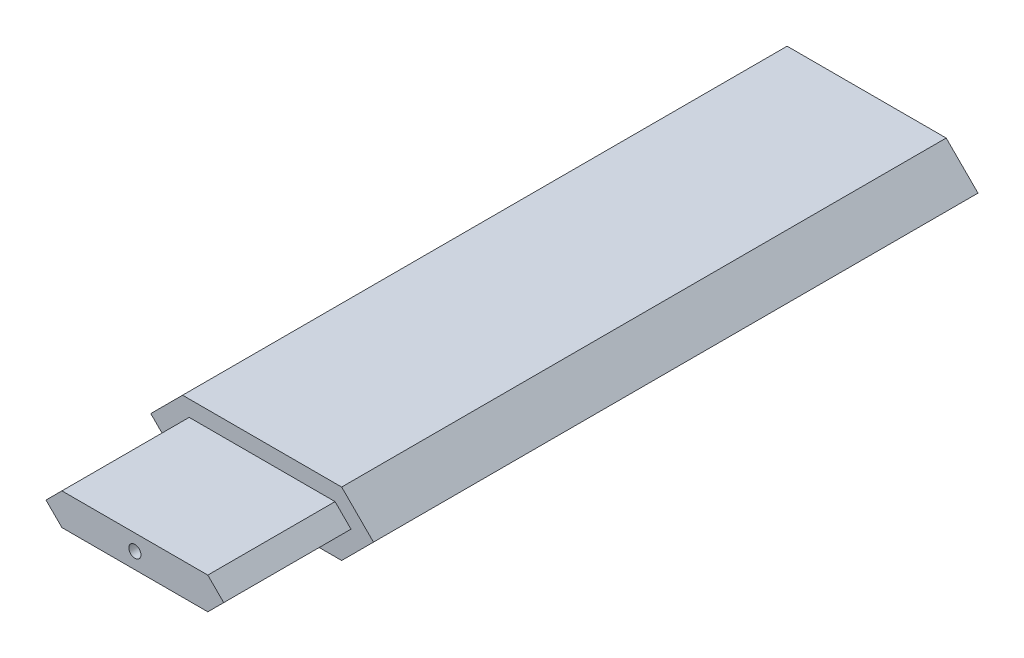
SolidWorks part; units mm, degrees
ref_plane "前视基准面" through (0, 0, 0) normal (0, 0, 1) x (1, 0, 0)
ref_plane "上视基准面" through (0, 0, 0) normal (0, 1, 0) x (1, 0, 0)
ref_plane "右视基准面" through (0, 0, 0) normal (1, 0, 0) x (0, 0, -1)
sketch "草图1" plane through (0, 0, 0) normal (0, 1, 0) x (1, 0, 0)
  line L0 (0, 0) -> (0, 690) construction
  line L1 (0, 690) -> (0, 630) construction
  line L2 (-35, 0) -> (35, 0)
  line L3 (-35, 0) -> (-35, 630)
  line L4 (-35, 630) -> (0, 690)
  line L5 (35, 630) -> (0, 690)
  line L6 (35, 0) -> (35, 630)
  dimension "D1" = 690
  dimension "D2" = 60
  dimension "D3" = 70
ref_plane "基准面1" through (0, 10, 0) normal (0, 1, 0) x (1, 0, 0)
sketch "草图4" plane through (0, 10, 0) normal (0, 1, 0) x (1, 0, 0)
  line L0 (25, 0) -> (-25, 0)
  line L1 (-25, 0) -> (-25, 630)
  line L2 (-25, 630) -> (0, 672.8571)
  line L3 (0, 0) -> (0, 690) construction
  line L4 (-35, 630) -> (0, 690) construction
  line L5 (0, -5.5) -> (0, 5.5) construction
  line L6 (25, 630) -> (0, 672.8571)
  line L7 (25, 0) -> (25, 630)
  point P2 (0, 0)
  dimension "D1" = 50
loft "放样1" add profiles "草图4", "草图1"
mirror "镜向1" about plane through (0, 0, 0) normal (0, 1, 0) of "放样1"
sketch "草图5" plane through (0, 0, 0) normal (0, 1, 0) x (1, 0, 0)
  line L0 (0, -30.5) -> (0, -55.5) construction
  line L1 (0, -55.5) -> (0, -30.5) construction
  line L2 (-79, -30.5) -> (79, -30.5) construction
  line L3 (0, -30.5) -> (0, 0) construction
  arc A0 (-66.3468, -65.1892) -> (66.3468, -65.1892) centre (0, -287.5) cw
  arc A1 (76.7912, -2.3877) -> (76.7912, -58.6123) centre (-101, -30.5) cw
  arc A2 (-76.7912, -2.3877) -> (-76.7912, -58.6123) centre (101, -30.5) ccw
  arc A4 (66.3468, -65.1892) -> (76.7912, -58.6123) centre (68.6918, -57.3316) ccw
  arc A5 (-66.3468, -65.1892) -> (-76.7912, -58.6123) centre (-68.6918, -57.3316) cw
  arc A6 (-76.7912, -2.3877) -> (76.7912, -2.3877) centre (0, 224.9955) ccw
  point P10 (0, -55.5)
  point P15 (79, -30.5)
  dimension "D4" = 232
  dimension "D5" = 180
  dimension "D6" = 8.2
  dimension "D7" = 240
  dimension "D1" = 25
  dimension "D2" = 158
  dimension "D3" = 30.5
extrude "凸台-拉伸1" add sketch "草图5" along normal mid plane 36 separate body
chamfer "倒角1" distance 5 angle 45 11 edges at (79, -18, 30.5) (73.0612, -18, 64.2705) (0, -18, 55.5) (-73.0612, -18, 64.2705) (-79, -18, 30.5) (79, 18, 30.5) (73.0612, 18, 64.2705) (0, 18, 55.5) (-73.0612, 18, 64.2705) (-79, 18, 30.5) (0, 18, 15.0045)
chamfer "倒角2" distance 5 angle 45 1 edges at (0, -18, 15.0045)
sketch "草图6" plane through (0, 18, 0) normal (0, 1, 0) x (1, 0, 0)
  arc A12 (67.2218, -55.0237) -> (68.3355, -15.4837) centre (-101, -30.5) ccw
  arc A13 (-68.3355, -15.4837) -> (68.3355, -15.4837) centre (0, 224.9955) ccw
  arc A14 (-68.3355, -15.4837) -> (-67.2218, -55.0237) centre (101, -30.5) ccw
  arc A15 (67.2218, -55.0237) -> (-67.2218, -55.0237) centre (0, -287.5) ccw
  arc A16 (67.2218, -55.0237) -> (68.3355, -15.4837) centre (-101, -30.5) ccw
  arc A17 (-68.3355, -15.4837) -> (68.3355, -15.4837) centre (0, 224.9955) ccw
  arc A18 (-68.3355, -15.4837) -> (-67.2218, -55.0237) centre (101, -30.5) ccw
  arc A19 (67.2218, -55.0237) -> (-67.2218, -55.0237) centre (0, -287.5) ccw
  dimension "D1" = 5
extrude "切除-拉伸1" cut sketch "草图6" against normal blind 8
mirror "镜向2" about plane through (0, 0, 0) normal (0, 1, 0) of "切除-拉伸1"
sketch "草图7" plane through (0, 0, 0) normal (0, 0, 1) x (1, 0, 0)
  line L12 (-25.8284, 12) -> (-37.8284, 0)
  line L13 (-37.8284, 0) -> (-25.8284, -12)
  line L14 (-25.8284, -12) -> (25.8284, -12)
  line L15 (25.8284, -12) -> (37.8284, 0)
  line L16 (37.8284, 0) -> (25.8284, 12)
  line L17 (25.8284, 12) -> (-25.8284, 12)
  line L18 (-25.8284, 12) -> (-37.8284, 0)
  line L19 (-37.8284, 0) -> (-25.8284, -12)
  line L20 (-25.8284, -12) -> (25.8284, -12)
  line L21 (25.8284, -12) -> (37.8284, 0)
  line L22 (37.8284, 0) -> (25.8284, 12)
  line L23 (25.8284, 12) -> (-25.8284, 12)
  dimension "D1" = 2
extrude "凸台-拉伸2" add sketch "草图7" along normal up to surface (12.0045 mm away)
sketch "草图8" plane through (0, 0, 0) normal (0, 0, -1) x (-1, 0, 0)
  line L6 (25.8284, 12) -> (-25.8284, 12)
  line L7 (-25.8284, 12) -> (-37.8284, 0)
  line L8 (-37.8284, 0) -> (-25.8284, -12)
  line L9 (-25.8284, -12) -> (25.8284, -12)
  line L10 (25.8284, -12) -> (37.8284, 0)
  line L11 (37.8284, 0) -> (25.8284, 12)
  line L12 (25.8284, 12) -> (-25.8284, 12)
  line L13 (-25.8284, 12) -> (-37.8284, 0)
  line L14 (-37.8284, 0) -> (-25.8284, -12)
  line L15 (-25.8284, -12) -> (25.8284, -12)
  line L16 (25.8284, -12) -> (37.8284, 0)
  line L17 (37.8284, 0) -> (25.8284, 12)
  dimension "D1" = 0
extrude "凸台-拉伸3" add sketch "草图8" along normal blind 5
sketch "草图9" plane through (0, 0, 0) normal (0, 1, 0) x (1, 0, 0)
  line L0 (0, 690) -> (0, -310) construction
  line L1 (0, -310) -> (0, -234)
  line L2 (0, -310) -> (0, -256) construction
  line L3 (-22.5, -256) -> (22.5, -256) construction
  line L4 (-22.5, -256) -> (0, -310)
  line L6 (-22.5, -256) -> (-12, -234)
  line L7 (-12, -234) -> (0, -234)
  dimension "D1" = 1000
  dimension "D2" = 76
  dimension "D3" = 54
  dimension "D4" = 45
  dimension "D5" = 12
revolve "旋转1" add sketch "草图9" angle 360 about L0
sketch "草图10" plane through (0, 0, 234) normal (0, 0, -1) x (-1, 0, 0)
  circle A1 centre (0, 0) radius 12
  circle A2 centre (0, 0) radius 12
  dimension "D1" = 0
extrude "凸台-拉伸4" add sketch "草图10" along normal up to next
sketch "草图16" plane through (0, 0, 0) normal (0, 1, 0) x (1, 0, 0)
  line L0 (0, 690) -> (0, -15.0045) construction
  line L1 (35, 630) -> (0, 690) construction
  line L2 (0, 0) -> (0, -20) construction
  line L3 (0, 5) -> (0, -35)
  line L4 (-50, 155) -> (50, 155)
  line L5 (-50, 155) -> (-50, 385)
  line L6 (-50, 385) -> (50, 385)
  line L7 (50, 155) -> (50, 385)
  line L8 (25.8284, 5) -> (-25.8284, 5) construction
  line L9 (0, -35) -> (0, 195)
  line L10 (0, 195) -> (0, 155)
  line L11 (0, 155) -> (0, 385)
  line L12 (0, 385) -> (0, 345)
  line L13 (0, 345) -> (0, 575)
  line L14 (0, 575) -> (0, 535)
  line L15 (0, 535) -> (0, 690)
  arc A0 (-25.8284, -13.6106) -> (25.8284, -13.6106) centre (0, 224.9955) ccw construction
  point P25 (0, 0)
  point P26 (0, 0)
  point P27 (0, 0)
  point P28 (0, 0)
  dimension "D7" = 40
  dimension "D1" = 40
  dimension "D2" = 20
  dimension "D3" = 100
  dimension "D4" = 230
  dimension "D5" = 40
  dimension "D6" = 230
  dimension "D8" = 230
  dimension "D9" = 40
extrude "切除-拉伸7" cut sketch "草图16" against normal through all both and the other way through all flip side to cut
sketch "草图21" plane through (0, 0, -155) normal (0, 0, 1) x (1, 0, 0)
  circle A0 centre (0, 0) radius 1.9
  dimension "D1" = 3.8
extrude "切除-拉伸17" cut sketch "草图21" against normal through all
sketch "草图34" plane through (0, 0, -155) normal (0, 0, 1) x (1, 0, 0)
  line L12 (-22.9289, -5) -> (22.9289, -5)
  line L13 (22.9289, -5) -> (27.9289, 0)
  line L14 (27.9289, 0) -> (22.9289, 5)
  line L15 (22.9289, 5) -> (-22.9289, 5)
  line L16 (-22.9289, 5) -> (-27.9289, 0)
  line L17 (-27.9289, 0) -> (-22.9289, -5)
  line L18 (-22.9289, -5) -> (22.9289, -5)
  line L19 (22.9289, -5) -> (27.9289, 0)
  line L20 (27.9289, 0) -> (22.9289, 5)
  line L21 (22.9289, 5) -> (-22.9289, 5)
  line L22 (-22.9289, 5) -> (-27.9289, 0)
  line L23 (-27.9289, 0) -> (-22.9289, -5)
  dimension "D1" = 5
extrude "切除-拉伸18" cut sketch "草图34" against normal blind 40 flip side to cut
sketch "草图35" plane through (0, 0, -385) normal (0, 0, -1) x (-1, 0, 0)
  line L12 (-28.2118, 0) -> (-23.0118, -5.2)
  line L13 (-23.0118, -5.2) -> (23.0118, -5.2)
  line L14 (23.0118, -5.2) -> (28.2118, 0)
  line L15 (28.2118, 0) -> (23.0118, 5.2)
  line L16 (23.0118, 5.2) -> (-23.0118, 5.2)
  line L17 (-23.0118, 5.2) -> (-28.2118, 0)
  line L18 (-28.2118, 0) -> (-23.0118, -5.2)
  line L19 (-23.0118, -5.2) -> (23.0118, -5.2)
  line L20 (23.0118, -5.2) -> (28.2118, 0)
  line L21 (28.2118, 0) -> (23.0118, 5.2)
  line L22 (23.0118, 5.2) -> (-23.0118, 5.2)
  line L23 (-23.0118, 5.2) -> (-28.2118, 0)
  dimension "D1" = 4.8
extrude "切除-拉伸19" cut sketch "草图35" against normal blind 41
